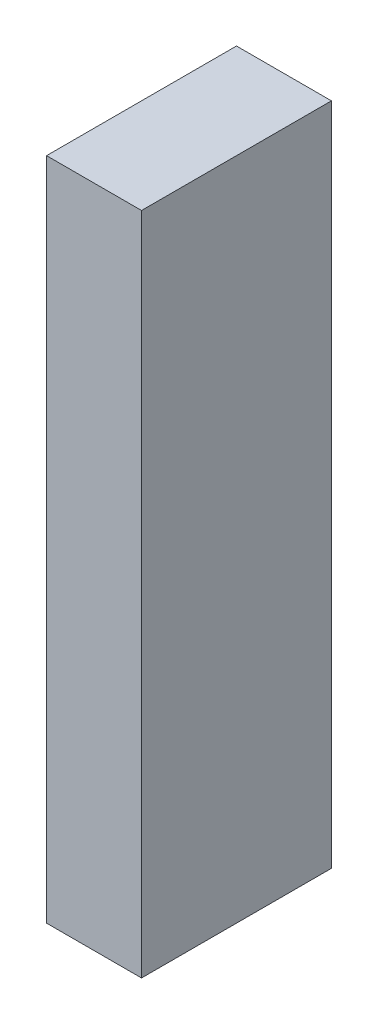
SolidWorks part; units mm, degrees
material "Teak"
ref_plane "Front Plane" through (0, 0, 0) normal (0, 0, 1) x (1, 0, 0)
ref_plane "Top Plane" through (0, 0, 0) normal (0, 1, 0) x (1, 0, 0)
ref_plane "Right Plane" through (0, 0, 0) normal (1, 0, 0) x (0, 0, -1)
sketch "Sketch1" plane through (0, 0, 0) normal (0, 1, 0) x (1, 0, 0)
  line L1 (-25.4, -50.8) -> (25.4, -50.8)
  line L2 (-25.4, -50.8) -> (-25.4, 50.8)
  line L3 (-25.4, 50.8) -> (25.4, 50.8)
  line L4 (25.4, -50.8) -> (25.4, 50.8)
  line L5 (-25.4, -50.8) -> (25.4, 50.8) construction
  line L6 (-25.4, 50.8) -> (25.4, -50.8) construction
  point P0 (0, 0)
  dimension "D1" = 50.8
  dimension "D2" = 101.6
extrude "Boss-Extrude1" add sketch "Sketch1" along normal blind 355.6
